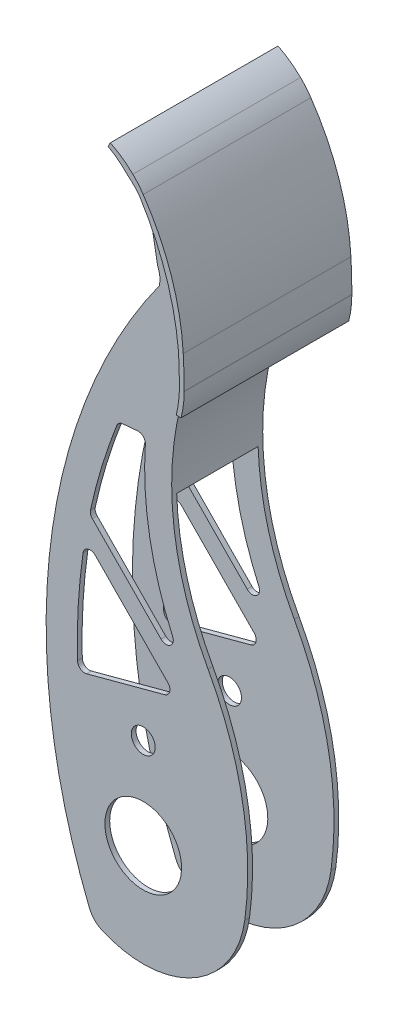
SolidWorks part; units mm, degrees
ref_plane "Front Plane" through (0, 0, 0) normal (0, 0, 1) x (1, 0, 0)
ref_plane "Top Plane" through (0, 0, 0) normal (0, 1, 0) x (1, 0, 0)
ref_plane "Right Plane" through (0, 0, 0) normal (1, 0, 0) x (0, 0, -1)
sketch "Sketch1" plane through (0, 0, 0) normal (0, 0, 1) x (1, 0, 0)
  line L0 (-18.4929, 133.0363) -> (-18.4985, 133.0259)
  line L1 (0.9178, 65.164) -> (0.9438, 65.164)
  line L3 (-27.9119, 139.6988) -> (-28.8599, 137.9378)
  line L5 (-0.3718, 55.0462) -> (1.6282, 55.0462)
  line L10 (-15.7949, 126.6815) -> (-27.9172, 110.1949)
  line L11 (-27.9172, 110.1949) -> (-24.1899, 89.2503)
  line L16 (-30.1705, -123.5527) -> (-30.1705, -85.5527) construction
  arc A4 (-20.8854, 131.7857) -> (-28.8599, 137.9378) centre (-43.7778, 110.3564) ccw
  arc A5 (-18.4985, 133.0259) -> (-27.9119, 139.6988) centre (-43.3787, 107.904) ccw
  arc A6 (-14.1877, 127.8743) -> (-18.4929, 133.0363) centre (-43.3747, 107.908) ccw
  arc A7 (-15.7949, 126.6815) -> (-20.8854, 131.7857) centre (-40.3956, 107.2373) ccw
  arc A8 (0.5208, 78.7822) -> (-15.7949, 126.6815) centre (-93.889, 73.3522) ccw
  arc A9 (0.9178, 65.164) -> (0.5208, 78.7822) centre (-239.7562, 64.9627) ccw
  arc A10 (2.9068, 65.3021) -> (2.5269, 78.7322) centre (-241.7672, 65.1007) ccw
  arc A11 (2.5269, 78.7322) -> (-14.1877, 127.8743) centre (-93.889, 73.3522) ccw
  arc A12 (2.9068, 65.1576) -> (2.9068, 65.3021) centre (-241.7672, 65.1576) ccw
  arc A13 (0.9438, 65.0196) -> (0.9438, 65.164) centre (-239.7303, 65.0196) ccw
  arc A14 (-0.3718, 55.0462) -> (0.9438, 65.0196) centre (-50.6612, 66.7533) ccw
  arc A15 (1.6282, 55.0462) -> (2.9068, 65.1576) centre (-38.0172, 65.1959) ccw
  arc A18 (0.5208, 78.7822) -> (-3.1243, -46.1571) centre (105.4142, 13.1991) ccw
  arc A19 (0.5208, 78.7822) -> (-15.7949, 126.6815) centre (-93.889, 73.3522) ccw
  arc A20 (-23.4728, 82.2249) -> (-24.1899, 89.2503) centre (-34.668, 84.6315) ccw
  arc A32 (-3.1243, -46.1571) -> (12.2054, -129.3514) centre (-121.7369, -111.0226) cw
  arc A33 (-47.4225, -162.6897) -> (12.2054, -129.3514) centre (-30.1705, -123.5527) ccw
  arc A38 (-23.4728, 82.2249) -> (-52.6672, -157.2694) centre (179.2903, -64.0186) ccw
  arc A39 (-47.4225, -162.6897) -> (-52.6672, -157.2694) centre (-43.3889, -153.5393) cw
  circle A40 centre (-30.1705, -123.5527) radius 16
  circle A41 centre (-30.1705, -85.5527) radius 5
  point P20 (-2.4666, 104.4473)
  dimension "D1" = 32
  dimension "D2" = 10
  dimension "D3" = 38
  dimension "D4" = 10
  dimension "D5" = 190
  dimension "D6" = 2
  dimension "D7" = 2
  dimension "D8" = 2
extrude "Boss-Extrude3" add sketch "Sketch1" along normal blind 70
sketch "Sketch4" plane through (0, 0, 0) normal (0, 0, -1) x (-1, 0, 0)
  line L2 (18.4985, 133.0259) -> (18.4929, 133.0363)
  line L3 (28.8599, 137.9378) -> (27.9119, 139.6988)
  line L5 (28.8599, 137.9378) -> (27.9119, 139.6988)
  line L6 (-0.9438, 65.164) -> (-0.9178, 65.164)
  line L7 (18.4985, 133.0259) -> (18.4929, 133.0363)
  line L8 (-0.9438, 65.164) -> (-0.9178, 65.164)
  line L9 (18.4985, 133.0259) -> (18.4929, 133.0363)
  line L10 (28.8599, 137.9378) -> (27.9119, 139.6988)
  line L12 (24.1899, 89.2503) -> (27.9172, 110.1949)
  line L17 (-1.6282, 55.0462) -> (0.3718, 55.0462)
  line L19 (-1.6282, 55.0462) -> (0.3718, 55.0462)
  line L20 (24.1899, 89.2503) -> (27.9172, 110.1949)
  line L21 (27.9172, 110.1949) -> (15.7949, 126.6815)
  line L22 (27.9172, 110.1949) -> (15.7949, 126.6815)
  line L23 (18.4985, 133.0259) -> (18.4929, 133.0363)
  line L24 (-1.6282, 55.0462) -> (0.3718, 55.0462)
  line L25 (-1.6282, 55.0462) -> (0.3718, 55.0462)
  line L26 (-0.9438, 65.164) -> (-0.9178, 65.164)
  line L27 (-0.9438, 65.164) -> (-0.9178, 65.164)
  line L28 (-1.6282, 55.0462) -> (0.3718, 55.0462)
  line L29 (-1.6282, 55.0462) -> (0.3718, 55.0462)
  line L30 (28.8599, 137.9378) -> (27.9119, 139.6988)
  line L31 (28.8599, 137.9378) -> (27.9119, 139.6988)
  line L32 (28.8599, 137.9378) -> (27.9119, 139.6988)
  line L33 (18.4985, 133.0259) -> (18.4929, 133.0363)
  line L34 (18.4985, 133.0259) -> (18.4929, 133.0363)
  line L35 (-0.9438, 65.164) -> (-0.9178, 65.164)
  line L36 (-0.9438, 65.164) -> (-0.9178, 65.164)
  arc A6 (28.8599, 137.9378) -> (20.8854, 131.7857) centre (43.7778, 110.3564) ccw
  arc A7 (27.9119, 139.6988) -> (18.4985, 133.0259) centre (43.3787, 107.904) ccw
  arc A8 (28.8599, 137.9378) -> (20.8854, 131.7857) centre (43.7778, 110.3564) ccw
  arc A9 (27.9119, 139.6988) -> (18.4985, 133.0259) centre (43.3787, 107.904) ccw
  arc A12 (-0.9438, 65.164) -> (-0.9438, 65.0196) centre (239.7303, 65.0196) ccw
  arc A13 (-0.9438, 65.0196) -> (0.3718, 55.0462) centre (50.6612, 66.7533) ccw
  arc A14 (-2.5269, 78.7322) -> (-2.9068, 65.3021) centre (241.7672, 65.1007) ccw
  arc A15 (14.1877, 127.8743) -> (-2.5269, 78.7322) centre (93.889, 73.3522) ccw
  arc A16 (18.4929, 133.0363) -> (14.1877, 127.8743) centre (43.3747, 107.908) ccw
  arc A17 (20.8854, 131.7857) -> (15.7949, 126.6815) centre (40.3956, 107.2373) ccw
  arc A18 (15.7949, 126.6815) -> (-0.5208, 78.7822) centre (93.889, 73.3522) ccw
  arc A19 (-0.5208, 78.7822) -> (-0.9178, 65.164) centre (239.7562, 64.9627) ccw
  arc A20 (-2.5269, 78.7322) -> (-2.9068, 65.3021) centre (241.7672, 65.1007) ccw
  arc A21 (14.1877, 127.8743) -> (-2.5269, 78.7322) centre (93.889, 73.3522) ccw
  arc A22 (18.4929, 133.0363) -> (14.1877, 127.8743) centre (43.3747, 107.908) ccw
  arc A23 (20.8854, 131.7857) -> (15.7949, 126.6815) centre (40.3956, 107.2373) ccw
  arc A25 (-0.5208, 78.7822) -> (-0.9178, 65.164) centre (239.7562, 64.9627) ccw
  arc A26 (-2.9068, 65.1576) -> (-1.6282, 55.0462) centre (38.0172, 65.1959) ccw
  arc A27 (-12.2054, -129.3514) -> (47.4225, -162.6897) centre (30.1705, -123.5527) ccw
  arc A28 (47.4225, -162.6897) -> (52.6672, -157.2694) centre (43.3889, -153.5393) ccw
  arc A29 (52.6672, -157.2694) -> (23.4728, 82.2249) centre (-179.2903, -64.0186) ccw
  arc A30 (15.7949, 126.6815) -> (-0.5208, 78.7822) centre (93.889, 73.3522) ccw
  arc A32 (3.1243, -46.1571) -> (-0.5208, 78.7822) centre (-105.4142, 13.1991) ccw
  arc A33 (3.1243, -46.1571) -> (-12.2054, -129.3514) centre (121.7369, -111.0226) ccw
  arc A34 (-12.2054, -129.3514) -> (47.4225, -162.6897) centre (30.1705, -123.5527) ccw
  arc A35 (47.4225, -162.6897) -> (52.6672, -157.2694) centre (43.3889, -153.5393) ccw
  arc A36 (52.6672, -157.2694) -> (23.4728, 82.2249) centre (-179.2903, -64.0186) ccw
  arc A39 (3.1243, -46.1571) -> (-0.5208, 78.7822) centre (-105.4142, 13.1991) ccw
  arc A40 (3.1243, -46.1571) -> (-12.2054, -129.3514) centre (121.7369, -111.0226) ccw
  arc A41 (-2.9068, 65.3021) -> (-2.9068, 65.1576) centre (241.7672, 65.1576) ccw
  arc A42 (-0.9438, 65.164) -> (-0.9438, 65.0196) centre (239.7303, 65.0196) ccw
  arc A43 (-0.9438, 65.0196) -> (0.3718, 55.0462) centre (50.6612, 66.7533) ccw
  arc A44 (-2.9068, 65.1576) -> (-1.6282, 55.0462) centre (38.0172, 65.1959) ccw
  arc A45 (-2.9068, 65.3021) -> (-2.9068, 65.1576) centre (241.7672, 65.1576) ccw
  arc A46 (24.1899, 89.2503) -> (23.4728, 82.2249) centre (34.668, 84.6315) ccw
  arc A47 (24.1899, 89.2503) -> (23.4728, 82.2249) centre (34.668, 84.6315) ccw
  arc A48 (15.7949, 126.6815) -> (-0.5208, 78.7822) centre (93.889, 73.3522) ccw
  arc A49 (15.7949, 126.6815) -> (-0.5208, 78.7822) centre (93.889, 73.3522) ccw
  arc A55 (15.7949, 126.6815) -> (-0.5208, 78.7822) centre (93.889, 73.3522) ccw
  arc A56 (15.7949, 126.6815) -> (-0.5208, 78.7822) centre (93.889, 73.3522) ccw
  arc A57 (20.8854, 131.7857) -> (15.7949, 126.6815) centre (40.3956, 107.2373) ccw
  arc A58 (20.8854, 131.7857) -> (15.7949, 126.6815) centre (40.3956, 107.2373) ccw
  arc A59 (18.4929, 133.0363) -> (14.1877, 127.8743) centre (43.3747, 107.908) ccw
  arc A60 (18.4929, 133.0363) -> (14.1877, 127.8743) centre (43.3747, 107.908) ccw
  arc A61 (14.1877, 127.8743) -> (-2.5269, 78.7322) centre (93.889, 73.3522) ccw
  arc A62 (14.1877, 127.8743) -> (-2.5269, 78.7322) centre (93.889, 73.3522) ccw
  arc A63 (-2.5269, 78.7322) -> (-2.9068, 65.3021) centre (241.7672, 65.1007) ccw
  arc A64 (-2.5269, 78.7322) -> (-2.9068, 65.3021) centre (241.7672, 65.1007) ccw
  arc A65 (-2.9068, 65.3021) -> (-2.9068, 65.1576) centre (241.7672, 65.1576) ccw
  arc A66 (-2.9068, 65.3021) -> (-2.9068, 65.1576) centre (241.7672, 65.1576) ccw
  arc A67 (-2.9068, 65.1576) -> (-1.6282, 55.0462) centre (38.0172, 65.1959) ccw
  arc A68 (-2.9068, 65.1576) -> (-1.6282, 55.0462) centre (38.0172, 65.1959) ccw
  arc A69 (-0.9438, 65.0196) -> (0.3718, 55.0462) centre (50.6612, 66.7533) ccw
  arc A70 (-0.9438, 65.0196) -> (0.3718, 55.0462) centre (50.6612, 66.7533) ccw
  arc A71 (-0.9438, 65.164) -> (-0.9438, 65.0196) centre (239.7303, 65.0196) ccw
  arc A72 (-0.9438, 65.164) -> (-0.9438, 65.0196) centre (239.7303, 65.0196) ccw
  arc A73 (-0.5208, 78.7822) -> (-0.9178, 65.164) centre (239.7562, 64.9627) ccw
  arc A74 (-0.5208, 78.7822) -> (-0.9178, 65.164) centre (239.7562, 64.9627) ccw
  arc A75 (-0.9438, 65.164) -> (-0.9438, 65.0196) centre (239.7303, 65.0196) ccw
  arc A76 (-0.9438, 65.164) -> (-0.9438, 65.0196) centre (239.7303, 65.0196) ccw
  arc A77 (-0.9438, 65.0196) -> (0.3718, 55.0462) centre (50.6612, 66.7533) ccw
  arc A78 (-0.9438, 65.0196) -> (0.3718, 55.0462) centre (50.6612, 66.7533) ccw
  arc A79 (-2.9068, 65.1576) -> (-1.6282, 55.0462) centre (38.0172, 65.1959) ccw
  arc A80 (-2.9068, 65.1576) -> (-1.6282, 55.0462) centre (38.0172, 65.1959) ccw
  arc A81 (-2.9068, 65.3021) -> (-2.9068, 65.1576) centre (241.7672, 65.1576) ccw
  arc A82 (-2.9068, 65.3021) -> (-2.9068, 65.1576) centre (241.7672, 65.1576) ccw
  arc A83 (27.9119, 139.6988) -> (18.4985, 133.0259) centre (43.3787, 107.904) ccw
  arc A84 (27.9119, 139.6988) -> (18.4985, 133.0259) centre (43.3787, 107.904) ccw
  arc A85 (28.8599, 137.9378) -> (20.8854, 131.7857) centre (43.7778, 110.3564) ccw
  arc A86 (28.8599, 137.9378) -> (20.8854, 131.7857) centre (43.7778, 110.3564) ccw
  arc A87 (15.7949, 126.6815) -> (-0.5208, 78.7822) centre (93.889, 73.3522) ccw
  arc A88 (15.7949, 126.6815) -> (-0.5208, 78.7822) centre (93.889, 73.3522) ccw
  arc A89 (20.8854, 131.7857) -> (15.7949, 126.6815) centre (40.3956, 107.2373) ccw
  arc A90 (20.8854, 131.7857) -> (15.7949, 126.6815) centre (40.3956, 107.2373) ccw
  arc A91 (28.8599, 137.9378) -> (20.8854, 131.7857) centre (43.7778, 110.3564) ccw
  arc A92 (28.8599, 137.9378) -> (20.8854, 131.7857) centre (43.7778, 110.3564) ccw
  arc A93 (27.9119, 139.6988) -> (18.4985, 133.0259) centre (43.3787, 107.904) ccw
  arc A94 (27.9119, 139.6988) -> (18.4985, 133.0259) centre (43.3787, 107.904) ccw
  arc A95 (18.4929, 133.0363) -> (14.1877, 127.8743) centre (43.3747, 107.908) ccw
  arc A96 (18.4929, 133.0363) -> (14.1877, 127.8743) centre (43.3747, 107.908) ccw
  arc A97 (14.1877, 127.8743) -> (-2.5269, 78.7322) centre (93.889, 73.3522) ccw
  arc A98 (14.1877, 127.8743) -> (-2.5269, 78.7322) centre (93.889, 73.3522) ccw
  arc A99 (-2.5269, 78.7322) -> (-2.9068, 65.3021) centre (241.7672, 65.1007) ccw
  arc A100 (-2.5269, 78.7322) -> (-2.9068, 65.3021) centre (241.7672, 65.1007) ccw
  arc A101 (-0.5208, 78.7822) -> (-0.9178, 65.164) centre (239.7562, 64.9627) ccw
  arc A102 (-0.5208, 78.7822) -> (-0.9178, 65.164) centre (239.7562, 64.9627) ccw
  dimension "D3" = 0
  dimension "D4" = 0
  dimension "D5" = 0
  dimension "D6" = 0
extrude "Cut-Extrude2" cut sketch "Sketch4" against normal blind 16
sketch "Sketch5" plane through (0, 0, 70) normal (0, 0, 1) x (1, 0, 0)
  line L0 (-15.7949, 126.6815) -> (-106.3447, 77.7155)
  line L1 (-106.3447, 77.7155) -> (-99.0568, -184.3569)
  line L2 (-99.0568, -184.3569) -> (38.7764, -199.7285)
  line L3 (38.7764, -199.7285) -> (9.5201, 37.7321)
  line L4 (9.5201, 37.7321) -> (-2.7319, 53.7205)
  line L5 (-2.7319, 53.7205) -> (0.5208, 78.7822)
  arc A0 (-15.7949, 126.6815) -> (0.5208, 78.7822) centre (-107.6552, 68.6631) cw
extrude "Cut-Extrude3" cut sketch "Sketch5" against normal blind 16
sketch "Sketch7" plane through (0, 0, 0) normal (1, 0, 0) x (0, 0, -1)
  line L0 (-70, 55.0462) -> (0, 55.0462) construction
  line L1 (-52, 55.0462) -> (-18, 55.0462)
  line L2 (-52, 55.0462) -> (-52, -196.5661)
  line L3 (-52, -196.5661) -> (-18, -196.5661)
  line L4 (-18, 55.0462) -> (-18, -196.5661)
  line L5 (-54, 78.7822) -> (-54, -46.1571) construction
  line L6 (-16, -46.1571) -> (-16, 78.7822) construction
  dimension "D1" = 2
  dimension "D2" = 2
extrude "Cut-Extrude4" cut sketch "Sketch7" against normal mid plane 175
sketch "Sketch8" plane through (0, 0, 52) normal (0, 0, -1) x (-1, 0, 0)
  line L1 (15.7949, 126.6815) -> (103.7274, 77.7155)
  line L2 (103.7274, 77.7155) -> (65.2012, -183.0775)
  line L3 (65.2012, -183.0775) -> (-41.3555, -162.7595)
  line L4 (-41.3555, -162.7595) -> (-12.0726, 35.4637)
  line L5 (-12.0726, 35.4637) -> (7.2537, 49.8149)
  line L6 (7.2537, 49.8149) -> (-0.5208, 78.7822)
  arc A0 (15.7949, 126.6815) -> (-0.5208, 78.7822) centre (105.0387, 69.5543) ccw
extrude "Cut-Extrude5" cut sketch "Sketch8" along normal blind 34
sketch "Sketch9" plane through (0, 0, 54) normal (0, 0, 1) x (1, 0, 0)
  line L2 (-8.3818, 61.7197) -> (-9.7526, 63.1759)
  line L3 (-18.2155, 8.7872) -> (-20.0491, 8.7217)
  arc A3 (-8.3818, 61.7197) -> (-18.2155, 8.7872) centre (105.4142, 13.1991) ccw
  arc A4 (0.5208, 78.7822) -> (-3.1243, -46.1571) centre (105.4142, 13.1991) ccw construction
  arc A5 (-9.7526, 63.1759) -> (-20.0491, 8.7217) centre (105.4142, 13.1991) ccw
  dimension "D1" = 2
extrude "Boss-Extrude4" add sketch "Sketch9" against normal blind 38
sketch "Sketch11" plane through (0, 0, 54) normal (0, 0, 1) x (1, 0, 0)
  line L0 (-50.185, -28.5983) -> (-19.8673, -59.4728)
  line L1 (-21.231, -64.4724) -> (-53.848, -73.2173)
  line L2 (-22.7627, -45.1062) -> (-51.4058, -15.9371)
  line L3 (-38.7032, 24.7037) -> (-32.5529, 25.2491)
  arc A0 (-57.6238, -70.4004) -> (-55.295, -30.2731) centre (179.2903, -64.0186) cw
  arc A1 (-19.8673, -59.4728) -> (-21.231, -64.4724) centre (-22.0079, -61.5747) cw
  arc A2 (-57.6238, -70.4004) -> (-53.848, -73.2173) centre (-54.6249, -70.3196) ccw
  arc A3 (-50.185, -28.5983) -> (-55.295, -30.2731) centre (-52.3256, -30.7002) ccw
  arc A4 (-52.1954, -13.1917) -> (-41.2296, 22.8145) centre (179.2903, -64.0186) cw
  arc A5 (-29.2944, 22.0638) -> (-17.8823, -41.7824) centre (105.4142, 13.1991) ccw
  arc A6 (-22.7627, -45.1062) -> (-17.8823, -41.7824) centre (-20.6222, -43.0042) ccw
  arc A7 (-52.1954, -13.1917) -> (-51.4058, -15.9371) centre (-49.2652, -13.8351) ccw
  arc A8 (-41.2296, 22.8145) -> (-38.7032, 24.7037) centre (-38.4382, 21.7154) cw
  arc A9 (-29.2944, 22.0638) -> (-32.5529, 25.2491) centre (-32.2879, 22.2608) ccw
  dimension "D1" = 3
  dimension "D2" = 237
  dimension "D3" = 135
  dimension "D4" = 3
  dimension "D6" = 237
  dimension "D5" = 8
extrude "Cut-Extrude6" cut sketch "Sketch11" against normal blind 135
